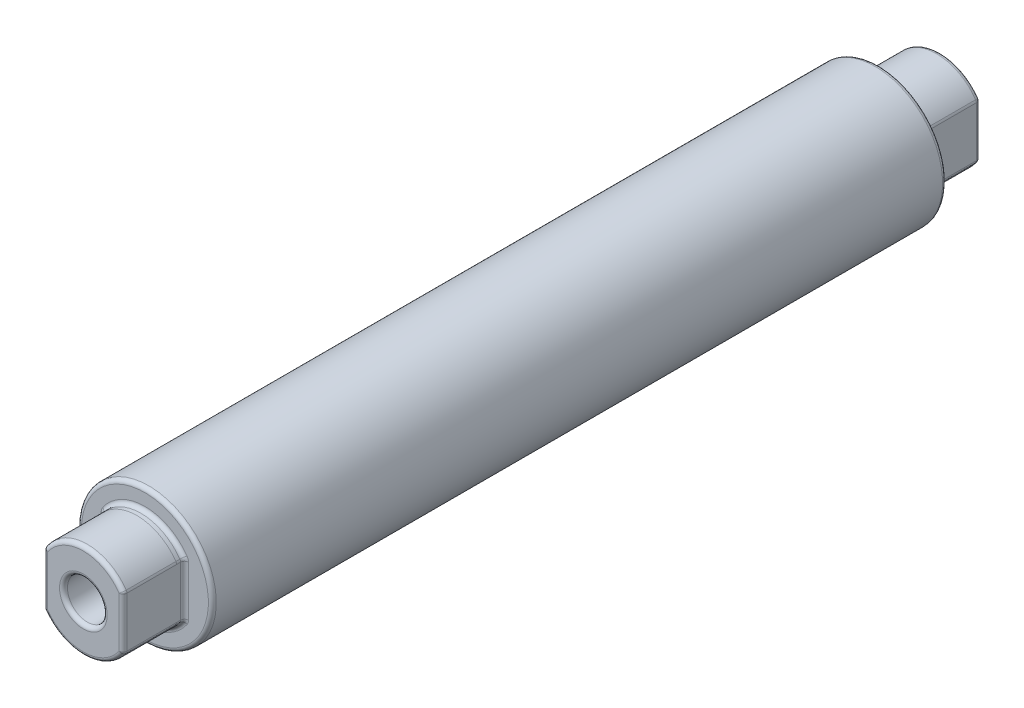
SolidWorks part; units mm, degrees
ref_plane "Alzado" through (0, 0, 0) normal (0, 0, 1) x (1, 0, 0)
ref_plane "Planta" through (0, 0, 0) normal (0, 1, 0) x (1, 0, 0)
ref_plane "Vista lateral" through (0, 0, 0) normal (1, 0, 0) x (0, 0, -1)
sketch "Croquis1" plane through (0, 0, 0) normal (1, 0, 0) x (0, 0, -1)
  line L0 (-55.0748, 0) -> (55.0748, 0) construction
  line L5 (-46.25, 8.5) -> (-46.25, 6)
  line L7 (-54, 6) -> (-54, 2.5)
  line L8 (-54, 2.5) -> (-46.25, 2.5)
  line L9 (0, 0) -> (0, 23.4689) construction
  line L12 (-46.25, 2.5) -> (0, 2.5)
  line L14 (-46.25, 8.5) -> (0, 8.5)
  line L16 (-46.25, 6) -> (-47.25, 6)
  line L17 (-47.25, 6) -> (-54, 6)
  line L18 (0, 8.5) -> (0, 2.5)
  dimension "D1" = 1
  dimension "D2" = 108
  dimension "D3" = 5
  dimension "D4" = 17
  dimension "D5" = 12
  dimension "D6" = 92.5
revolve "Revolución4" add sketch "Croquis1" angle 360 about L0
sketch "Croquis2" plane through (0, 0, 0) normal (1, 0, 0) x (0, 0, -1)
  line L0 (-47.25, -6) -> (-47.25, 6)
  line L2 (-54, -6) -> (-46.25, -6) construction
  point P3 (-47.25, 0)
split line "Línea de partición1"
sketch "Croquis3" plane through (0, 0, 54) normal (0, 0, 1) x (1, 0, 0)
  line L1 (-5, 3.3166) -> (5, 3.3166) construction
  line L2 (-5, 3.3166) -> (-5, -3.3166)
  line L3 (-5, -3.3166) -> (5, -3.3166) construction
  line L4 (5, 3.3166) -> (5, -3.3166)
  line L5 (-5, 3.3166) -> (5, -3.3166) construction
  line L6 (-5, -3.3166) -> (5, 3.3166) construction
  circle A0 centre (0, 0) radius 6 construction
  circle A1 centre (0, 0) radius 6 construction
  arc A2 (-5, 3.3166) -> (-5, -3.3166) centre (0, 0) ccw
  arc A3 (5, -3.3166) -> (5, 3.3166) centre (0, 0) ccw
  point P0 (0, 0)
  dimension "D1" = 10
extrude "Cortar-Extruir1" cut sketch "Croquis3" against normal up to surface (7.75 mm away) up to face at (6, 0, 46.25)
fillet "Redondeo2" radius 0.5 16 edges at (-5, 0, 46.25) (0, 6, 46.25) (0, -6, 54) (0, -6, 46.25) (0, 6, 54) (-5, 3.3166, 50.625) (-5, 3.3166, 46.75) (5, 3.3166, 46.75) (5, 3.3166, 50.625) (5, -3.3166, 50.625) (5, -3.3166, 46.75) (5, 0, 54) (-5, 0, 54) (5, 0, 46.25) (8.5, 0, 46.25) (2.5, 0, 54)
mirror "Simetría1" about plane through (0, 0, 0) normal (0, 0, 1) of bodies 106
